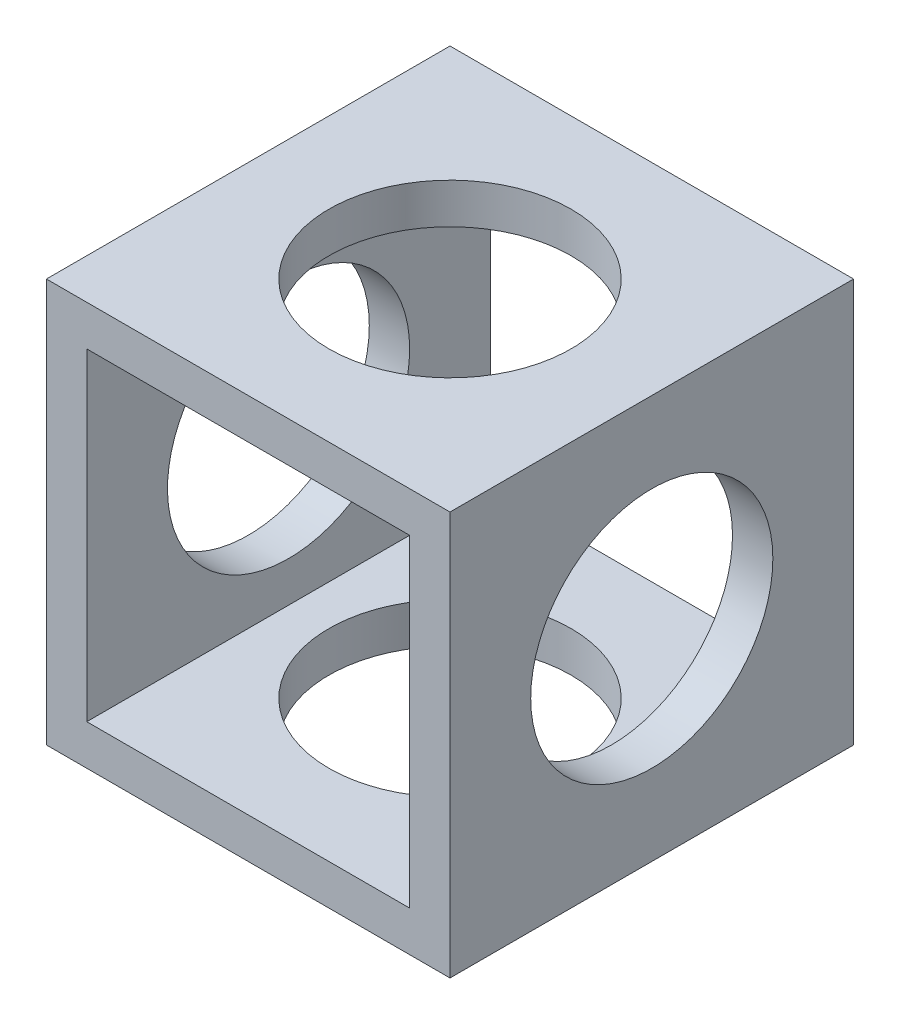
SolidWorks part; units mm, degrees
ref_plane "Alzado" through (0, 0, 0) normal (0, 0, 1) x (1, 0, 0)
ref_plane "Planta" through (0, 0, 0) normal (0, 1, 0) x (1, 0, 0)
ref_plane "Vista lateral" through (0, 0, 0) normal (1, 0, 0) x (0, 0, -1)
sketch "Croquis1" plane through (0, 0, 0) normal (0, 0, 1) x (1, 0, 0)
  line L0 (-20, 20) -> (20, 20)
  line L1 (-25, 25) -> (25, 25)
  line L2 (-25, 25) -> (-25, -25)
  line L3 (-25, -25) -> (25, -25)
  line L4 (25, 25) -> (25, -25)
  line L5 (-25, 25) -> (25, -25) construction
  line L6 (-25, -25) -> (25, 25) construction
  line L7 (20, 20) -> (20, -20)
  line L8 (-20, -20) -> (20, -20)
  line L9 (-20, 20) -> (-20, -20)
  point P0 (0, 0)
  dimension "D1" = 50
  dimension "D2" = 50
  dimension "D3" = 5
extrude "Saliente-Extruir1" add sketch "Croquis1" along normal mid plane 50
hole_wizard "Taladro1" positions "Croquis2" profile "Croquis3" legacy end condition through all
sketch "Croquis2" plane through (25, 0, 0) normal (1, 0, 0) x (0, 0, -1)
  point P0 (0, 0)
sketch "Croquis3" plane through (25, 0, 0) normal (0, 1, 0) x (0, 0, -1)
  line L0 (0, 0) -> (0, 50)
  line L1 (0, 50) -> (15, 50)
  line L2 (15, 50) -> (15, 0)
  line L3 (15, 0) -> (0, 0)
  line L4 (0, 110) -> (0, -10) construction
  dimension "Diámetro" = 30
  dimension "Profundidad" = 50
hole_wizard "Taladro3" positions "Croquis6" profile "Croquis7" legacy
sketch "Croquis6" plane through (0, -20, 0) normal (0, 1, 0) x (1, 0, 0)
  point P0 (0, 0)
sketch "Croquis7" plane through (0, -20, 0) normal (1, 0, 0) x (0, 0, 1)
  line L0 (0, 0) -> (0, 5)
  line L1 (0, 5) -> (15, 5)
  line L2 (15, 5) -> (15, 0)
  line L3 (15, 0) -> (0, 0)
  line L4 (0, 110) -> (0, -10) construction
  dimension "Diámetro" = 30
  dimension "Profundidad" = 5
hole_wizard "Taladro4" positions "Croquis8" profile "Croquis9" legacy end condition through all
sketch "Croquis8" plane through (0, 25, 0) normal (0, 1, 0) x (1, 0, 0)
  point P0 (0, 0)
sketch "Croquis9" plane through (0, 25, 0) normal (1, 0, 0) x (0, 0, 1)
  line L0 (0, 0) -> (0, 50)
  line L1 (0, 50) -> (15, 50)
  line L2 (15, 50) -> (15, 0)
  line L3 (15, 0) -> (0, 0)
  line L4 (0, 110) -> (0, -10) construction
  dimension "Diámetro" = 30
  dimension "Profundidad" = 50
